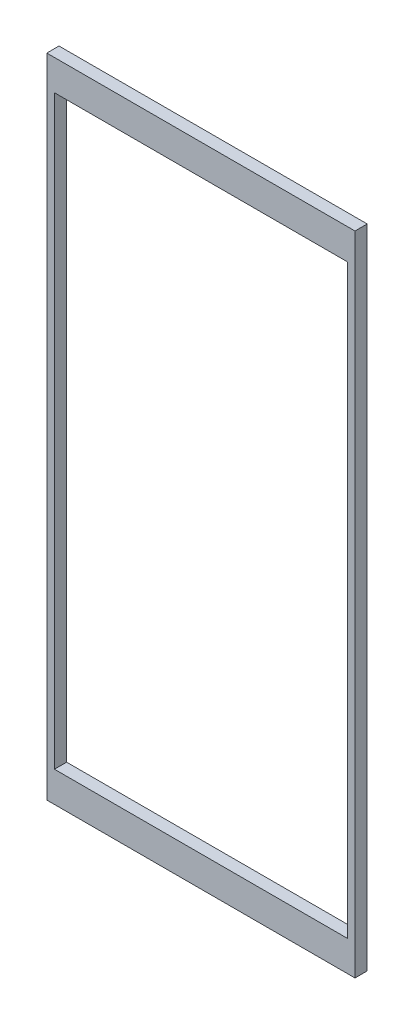
SolidWorks part; units mm, degrees
ref_plane "Front Plane" through (0, 0, 0) normal (0, 0, 1) x (1, 0, 0)
ref_plane "Top Plane" through (0, 0, 0) normal (0, 1, 0) x (1, 0, 0)
ref_plane "Right Plane" through (0, 0, 0) normal (1, 0, 0) x (0, 0, -1)
sketch "Sketch1" plane through (0, 0, 0) normal (0, 0, 1) x (1, 0, 0)
  line L1 (0, 0) -> (202, 0)
  line L2 (0, 0) -> (0, 424)
  line L3 (0, 424) -> (202, 424)
  line L4 (202, 0) -> (202, 424)
  dimension "D1" = 202
  dimension "D2" = 424
extrude "Boss-Extrude1" add sketch "Sketch1" along normal blind 8
sketch "Sketch2" plane through (0, 0, 0) normal (0, 0, -1) x (-1, 0, 0)
  line L0 (-202, 0) -> (-202, 424) construction
  line L1 (-197, 404) -> (-5, 404)
  line L2 (-197, 404) -> (-197, 20)
  line L3 (-197, 20) -> (-5, 20)
  line L4 (-5, 404) -> (-5, 20)
  line L5 (0, 424) -> (0, 0) construction
  line L6 (-202, 424) -> (0, 424) construction
  line L7 (0, 0) -> (-202, 0) construction
  dimension "D1" = 5
  dimension "D2" = 5
  dimension "D3" = 20
  dimension "D4" = 20
extrude "Cut-Extrude1" cut sketch "Sketch2" against normal through all
sketch "Sketch4" plane through (0, 0, 0) normal (0, 0, -1) x (-1, 0, 0)
  line L0 (-202, 0) -> (-202, 424) construction
  line L1 (-202, 424) -> (0, 424) construction
  line L2 (0, 424) -> (0, 0) construction
  circle A0 centre (-184, 414) radius 2
  circle A1 centre (-18, 414) radius 2
  circle A2 centre (-101, 414) radius 2
  dimension "D1" = 4
  dimension "D2" = 4
  dimension "D3" = 4
  dimension "D4" = 18
  dimension "D5" = 10
  dimension "D6" = 18
  dimension "D7" = 10
  dimension "D8" = 10
  dimension "D9" = 101
extrude "Cut-Extrude2" cut sketch "Sketch4" against normal blind 4.78
ref_plane "Plane1" through (0, 212, 0) normal (0, 1, 0) x (1, 0, 0)
mirror "Mirror1" about plane through (0, 212, 0) normal (0, 1, 0) of "Cut-Extrude2"
